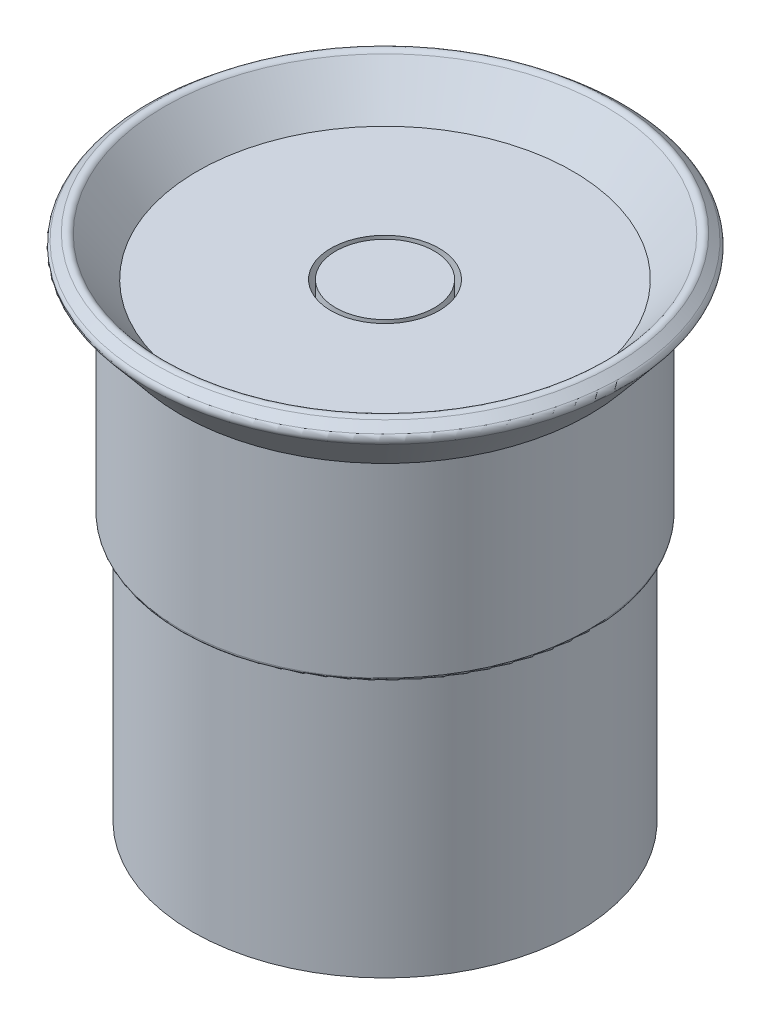
SolidWorks part; units mm, degrees
ref_plane "Plano frontal" through (0, 0, 0) normal (0, 0, 1) x (1, 0, 0)
ref_plane "Plano superior" through (0, 0, 0) normal (0, 1, 0) x (1, 0, 0)
ref_plane "Plano direito" through (0, 0, 0) normal (1, 0, 0) x (0, 0, -1)
sketch "Esboço1" plane through (0, 0, 0) normal (0, 1, 0) x (1, 0, 0)
  circle A0 centre (0, 0) radius 16
  circle A1 centre (0, 0) radius 14
  dimension "D1" = 32
  dimension "D2" = 28
extrude "Ressalto-extrusão1" add sketch "Esboço1" along normal blind 22
sketch "Esboço2" plane through (0, 22, 0) normal (0, 1, 0) x (1, 0, 0)
  circle A0 centre (0, 0) radius 17
  dimension "D1" = 34
extrude "Ressalto-extrusão2" add sketch "Esboço2" along normal blind 17
sketch "Esboço3" plane through (0, 39, 0) normal (0, 1, 0) x (1, 0, 0)
  circle A0 centre (0, 0) radius 4.5
  dimension "D1" = 9
extrude "Corte-extrusão1" cut sketch "Esboço3" against normal through all
fillet "Filete1" radius 0.3 2 edges at (0, 22, 17) (0, 39, 17)
sketch "Esboço4" plane through (0, 39, 0) normal (0, 1, 0) x (1, 0, 0)
  circle A0 centre (0, 0) radius 4.0954
extrude "Ressalto-extrusão3" add sketch "Esboço4" against normal blind 3 separate body
sketch "Esboço5" plane through (0, 0, 0) normal (0, 0, 1) x (1, 0, 0)
  line L0 (0, 39) -> (0, 45.4842) construction
  line L1 (4.0954, 39) -> (-4.0954, 39) construction
  line L2 (15.6063, 39) -> (18.6535, 42.6702)
  line L3 (16.7, 39) -> (-16.7, 39) construction
  line L4 (18.6535, 42.6702) -> (20.0858, 41.481)
  line L5 (20.0858, 41.481) -> (17, 37.7644)
  line L6 (17, 22.3) -> (17, 38.7) construction
  line L7 (17, 37.7644) -> (15.6063, 39)
revolve "Revolução1" add sketch "Esboço5" angle 360 about L0
fillet "Filete2" radius 0.5 2 edges at (0, 41.481, -20.0858) (0, 42.6702, -18.6535)
